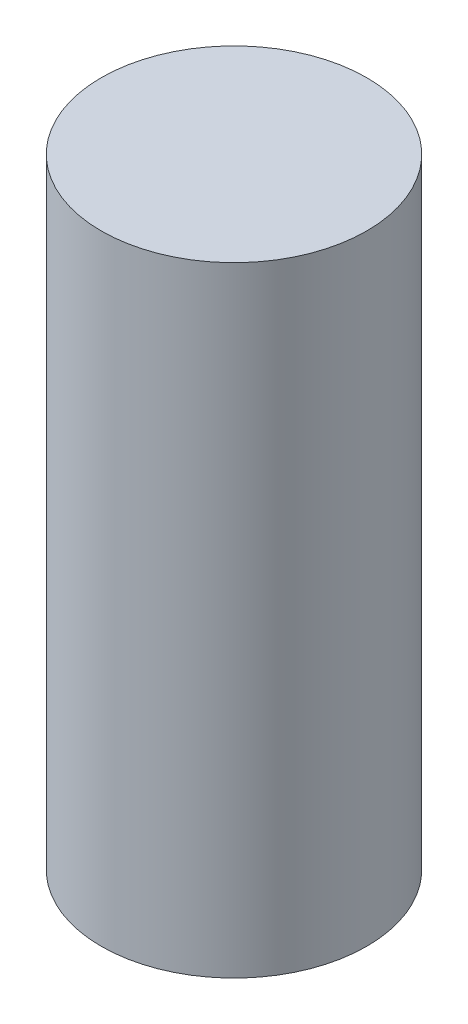
SolidWorks part; units mm, degrees
ref_plane "Front Plane" through (0, 0, 0) normal (0, 0, 1) x (1, 0, 0)
ref_plane "Top Plane" through (0, 0, 0) normal (0, 1, 0) x (1, 0, 0)
ref_plane "Right Plane" through (0, 0, 0) normal (1, 0, 0) x (0, 0, -1)
other "Configuration Table"
sketch "Sketch1" plane through (0, 0, 0) normal (0, 1, 0) x (1, 0, 0)
  circle A0 centre (650, 50) radius 6
extrude "OVEN_ayar_mil_2" add sketch "Sketch1" along normal blind 28 from offset 12 separate body
